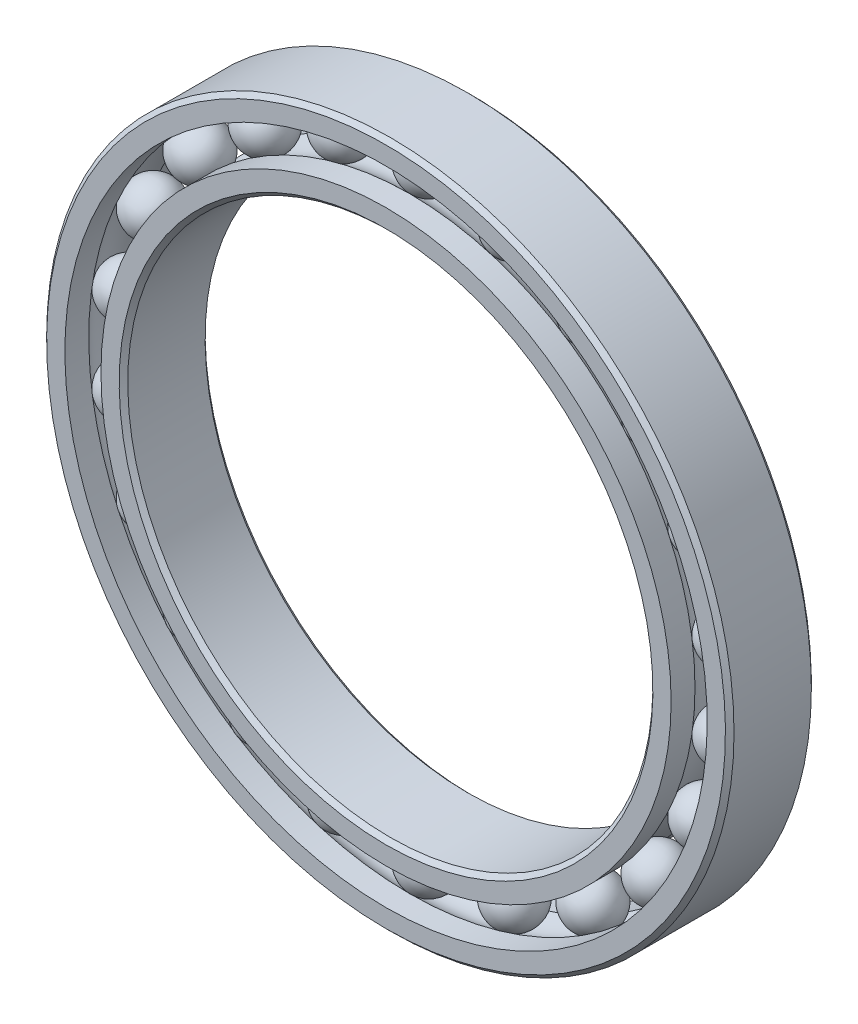
SolidWorks part; units mm, degrees
ref_plane "Front Plane" through (0, 0, 0) normal (0, 0, 1) x (1, 0, 0)
ref_plane "Top Plane" through (0, 0, 0) normal (0, 1, 0) x (1, 0, 0)
ref_plane "Right Plane" through (0, 0, 0) normal (1, 0, 0) x (0, 0, -1)
sketch "Sketch1" plane through (0, 0, 0) normal (0, 0, 1) x (1, 0, 0)
  circle A0 centre (0, 0) radius 36
  circle A1 centre (0, 0) radius 27.5
  dimension "OD" = 72
  dimension "ID" = 55
  dimension "For Shaft Diameter" = 55
  dimension "For Housing ID" = 72
sketch "Sketch5" plane through (0, 0, 0) normal (1, 0, 0) x (0, 0, -1)
  line L0 (-4.5, 0) -> (4.5, 0) construction
  line L1 (0, 36) -> (0, -36) construction
  line L2 (4.05, 36) -> (-4.05, 36)
  line L3 (-4.05, 36) -> (-4.5, 35.55)
  line L4 (-4.5, 35.55) -> (-4.5, 33.6389)
  line L5 (-4.5, 33.6389) -> (-2, 33.6389)
  line L6 (4.5, 33.6389) -> (2, 33.6389)
  line L7 (4.5, 35.55) -> (4.5, 33.6389)
  line L8 (4.05, 36) -> (4.5, 35.55)
  line L9 (0, 36) -> (0, 31.75) construction
  line L10 (0, 31.75) -> (0, 27.5) construction
  line L11 (-2.751, 31.75) -> (-4.5, 31.75) construction
  line L12 (3.435, 29.8865) -> (3.816, 29.8865) construction
  line L13 (-3.435, 29.8865) -> (-3.816, 29.8865) construction
  line L14 (-3.435, 29.8865) -> (-3.435, 33.6135) construction
  line L15 (-3.435, 33.6135) -> (-3.816, 33.6135) construction
  line L16 (-3.816, 29.8865) -> (-3.816, 33.6135) construction
  line L17 (-3.435, 29.8865) -> (-3.816, 33.6135) construction
  line L18 (-3.435, 33.6135) -> (-3.816, 29.8865) construction
  line L19 (3.816, 29.8865) -> (3.816, 33.6135) construction
  line L20 (3.435, 33.6135) -> (3.816, 33.6135) construction
  line L21 (3.435, 29.8865) -> (3.435, 33.6135) construction
  line L22 (0, 36) -> (0, -36) construction
  arc A0 (-2, 33.6389) -> (2, 33.6389) centre (0, 31.75) cw
  circle A1 centre (0, 31.75) radius 2.751 construction
  point P14 (0, 27.5)
  point P15 (-3.6255, 31.75)
  dimension "D1" = 45
  dimension "D2" = 0.45
  dimension "D3" = 4
  dimension "D4" = 1.8889
  dimension "D5" = 0.381
  dimension "D6" = 0.0254
  dimension "Width" = 9
sketch "Sketch6" plane through (0, 0, 0) normal (1, 0, 0) x (0, 0, -1)
  line L0 (4.05, 36) -> (4.5, 35.55) construction
  line L1 (4.5, 35.55) -> (4.5, 33.6389) construction
  line L2 (4.5, 33.6389) -> (2, 33.6389) construction
  line L3 (-4.5, 33.6389) -> (-2, 33.6389) construction
  line L4 (-4.5, 35.55) -> (-4.5, 33.6389) construction
  line L5 (-4.05, 36) -> (-4.5, 35.55) construction
  line L6 (4.05, 36) -> (-4.05, 36) construction
  line L7 (4.05, 36) -> (4.5, 35.55)
  line L8 (4.5, 35.55) -> (4.5, 33.6389)
  line L9 (4.5, 33.6389) -> (2, 33.6389)
  line L10 (-4.5, 33.6389) -> (-2, 33.6389)
  line L11 (-4.5, 35.55) -> (-4.5, 33.6389)
  line L12 (-4.05, 36) -> (-4.5, 35.55)
  line L13 (4.05, 36) -> (-4.05, 36)
  arc A0 (2, 33.6389) -> (-2, 33.6389) centre (0, 31.75) ccw construction
  arc A1 (2, 33.6389) -> (-2, 33.6389) centre (0, 31.75) ccw
revolve "Revolve5" add sketch "Sketch6" angle 360 about L0
sketch "Sketch3" plane through (0, 0, 0) normal (1, 0, 0) x (0, 0, -1)
  line L0 (-4.5, 29.8611) -> (-2, 29.8611)
  line L1 (0, 36) -> (0, -36) construction
  line L2 (-4.5, 35.55) -> (-4.5, 33.6389) construction
  line L3 (-4.5, 29.8611) -> (-4.5, 27.95)
  line L4 (-4.05, 36) -> (-4.5, 35.55) construction
  line L5 (-4.5, 27.95) -> (-4.05, 27.5)
  line L6 (-4.05, 27.5) -> (4.05, 27.5)
  line L8 (4.05, 27.5) -> (4.5, 27.95)
  line L10 (4.5, 27.95) -> (4.5, 29.8611)
  line L11 (4.5, 29.8611) -> (2, 29.8611)
  line L12 (4.05, 36) -> (4.05, -36) construction
  line L13 (4.05, 36) -> (4.5, 35.55) construction
  line L14 (4.5, -35.55) -> (4.5, 35.55) construction
  arc A0 (2, 33.6389) -> (-2, 33.6389) centre (0, 31.75) ccw construction
  arc A1 (2, 29.8611) -> (-2, 29.8611) centre (0, 31.75) cw
revolve "Revolve3" add sketch "Sketch3" angle 360 about L0
sketch "Sketch4" plane through (0, 0, 0) normal (1, 0, 0) x (0, 0, -1)
  line L0 (-2.751, 31.75) -> (2.751, 31.75)
  arc A2 (-2.751, 31.75) -> (2.751, 31.75) centre (0, 31.75) cw
  arc A3 (2, 33.6389) -> (-2, 33.6389) centre (0, 31.75) ccw construction
revolve "Revolve4" add sketch "Sketch4" angle 360 about L0
pattern_circular "CirPattern1" count 22 over 360 about axis through (0, 0, 0) along (0, 0, 1) of bodies 104
equation "\"D2@Sketch5\" = \"Width@Sketch5\" * .05"
equation "\"D3@Sketch5\" = \"Width@Sketch5\" / 2.25"
equation "\"D4@Sketch5\"=((\"OD@Sketch1\"-\"ID@Sketch1\")/2)/4.5"
